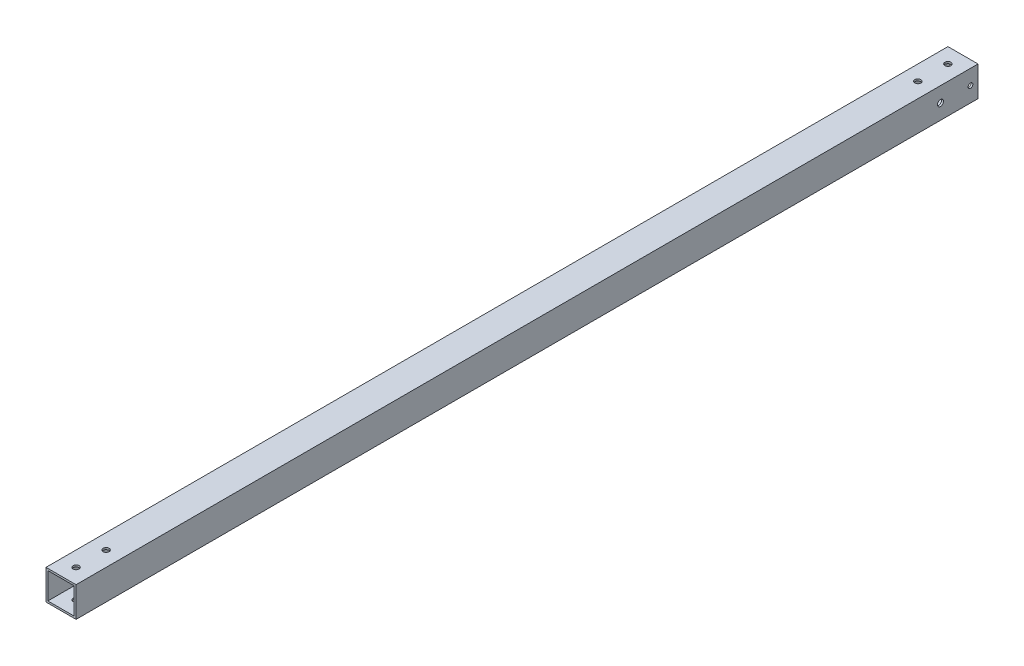
SolidWorks part; units mm, degrees
ref_plane "Front Plane" through (0, 0, 0) normal (0, 0, 1) x (1, 0, 0)
ref_plane "Top Plane" through (0, 0, 0) normal (0, 1, 0) x (1, 0, 0)
ref_plane "Right Plane" through (0, 0, 0) normal (1, 0, 0) x (0, 0, -1)
sketch "Sketch1" plane through (0, 0, 0) normal (0, 0, 1) x (1, 0, 0)
  line L1 (0, 0) -> (25.4, 0)
  line L2 (0, 0) -> (0, 25.4)
  line L3 (0, 25.4) -> (25.4, 25.4)
  line L4 (25.4, 0) -> (25.4, 25.4)
  line L5 (1.5875, 1.5875) -> (23.8125, 1.5875)
  line L6 (1.5875, 1.5875) -> (1.5875, 23.8125)
  line L7 (1.5875, 23.8125) -> (23.8125, 23.8125)
  line L8 (23.8125, 1.5875) -> (23.8125, 23.8125)
  dimension "D1" = 25.4
  dimension "D2" = 1.5875
  dimension "D3" = 1.5875
  dimension "D4" = 1.5875
  dimension "D5" = 1.5875
extrude "Boss-Extrude1" add sketch "Sketch1" along normal blind 762
sketch "Sketch3" plane through (0, 25.4, 0) normal (0, 1, 0) x (1, 0, 0)
  line L0 (0, -381) -> (25.4, -381) construction
  line L1 (25.4, -762) -> (25.4, 0) construction
  line L2 (25.4, 0) -> (0, 0) construction
  line L4 (0, -762) -> (0, 0) construction
  circle A1 centre (12.7, -12.7) radius 2.54
  circle A5 centre (12.7, -38.1) radius 2.54
  circle A12 centre (12.7, -723.9) radius 2.54
  circle A13 centre (12.7, -749.3) radius 2.54
  dimension "D1" = 5.08
  dimension "D4" = 12.7
  dimension "D7" = 25.4
extrude "Cut-Extrude2" cut sketch "Sketch3" against normal through all
sketch "Sketch4" plane through (25.4, 0, 0) normal (1, 0, 0) x (0, 0, -1)
  line L2 (0, 0) -> (0, 25.4) construction
  line L3 (-762, 25.4) -> (0, 25.4) construction
  circle A1 centre (-6.35, 12.7) radius 2.0034
  circle A2 centre (-31.75, 12.7) radius 2.54
  dimension "D3" = 6.35
  dimension "D1" = 5.08
  dimension "D2" = 25.4
  dimension "D4" = 12.7
extrude "Cut-Extrude3" cut sketch "Sketch4" against normal up to next
sketch "Sketch5" plane through (0, 0, 0) normal (-1, 0, 0) x (0, 0, 1)
  line L0 (0, 12.7) -> (762, 12.7) construction
  line L1 (0, 25.4) -> (0, 0) construction
  line L2 (762, 25.4) -> (762, 0) construction
  line L3 (381, 25.4) -> (381, 0) construction
  line L4 (762, 25.4) -> (0, 25.4) construction
  line L5 (762, 0) -> (0, 0) construction
  circle A0 centre (39.6875, 12.7) radius 2.54
  circle A1 centre (722.3125, 12.7) radius 2.54
  point P14 (0, 0)
  dimension "D1" = 5.08
  dimension "D2" = 39.6875
extrude "Cut-Extrude4" cut sketch "Sketch5" against normal up to next
